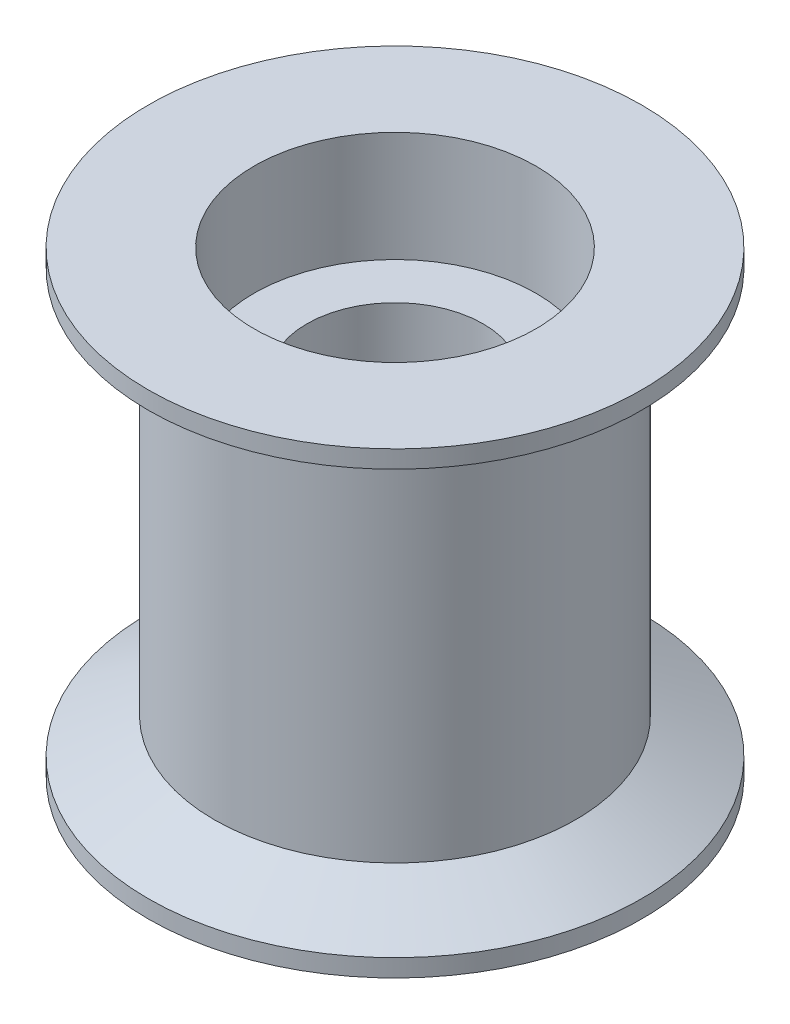
SolidWorks part; units mm, degrees
material "Markforged"
ref_plane "Front Plane" through (0, 0, 0) normal (0, 0, 1) x (1, 0, 0)
ref_plane "Top Plane" through (0, 0, 0) normal (0, 1, 0) x (1, 0, 0)
ref_plane "Right Plane" through (0, 0, 0) normal (1, 0, 0) x (0, 0, -1)
other "Bounding Box"
ref_plane "Default Plane" through (-8.9266, -12.7485, 0) normal (-0.1736, 0.9848, 0) x (0.9848, 0.1736, 0)
sketch "Sketch2" plane through (0, 0, 0) normal (1, 0, 0) x (0, 0, -1)
  line L0 (0, 0) -> (196218.8196, 0) construction
  line L1 (0, 0) -> (0, 196218.8196) construction
  line L2 (2.5, 0) -> (2.5, 3.375)
  line L3 (2.5, 3.375) -> (4, 3.375)
  line L4 (4, 3.375) -> (4, 6.5)
  line L5 (4, 6.5) -> (7, 6.5)
  line L6 (7, 6.5) -> (7, 6)
  line L7 (7, 6) -> (5.125, 5)
  line L8 (5.125, 5) -> (5.125, 0)
  line L9 (5.125, 0) -> (2.5, 0)
  point P7 (5.7095, 2.7622)
  point P14 (6.8607, 3.507)
  point P15 (7, 6.1271)
  point P16 (7, 6.9088)
  point P17 (4, 3.8304)
  dimension "D1" = 5
  dimension "D2" = 8
  dimension "D3" = 3.125
  dimension "D4" = 10.25
  dimension "D5" = 14
  dimension "D6" = 10
  dimension "D7" = 0.5
  dimension "D8" = 1.5
revolve "Revolve1" add sketch "Sketch2" angle 360 about L1
mirror "Mirror1" about plane through (0, 0, 0) normal (0, 1, 0) of "Revolve1"
